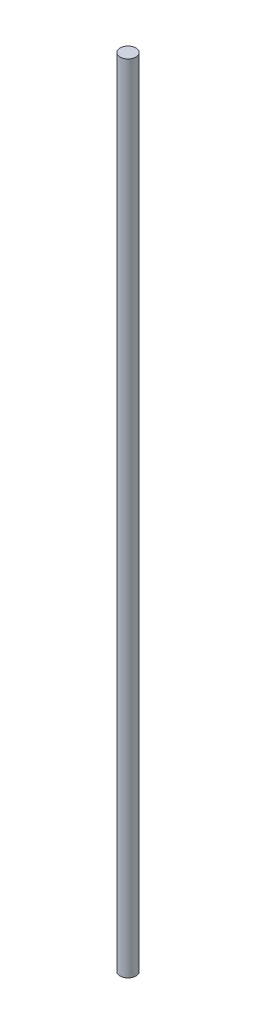
SolidWorks part; units mm, degrees
ref_plane "前视基准面" through (0, 0, 0) normal (0, 0, 1) x (1, 0, 0)
ref_plane "上视基准面" through (0, 0, 0) normal (0, 1, 0) x (1, 0, 0)
ref_plane "右视基准面" through (0, 0, 0) normal (1, 0, 0) x (0, 0, -1)
sketch "Sketch1" plane through (0, 0, 0) normal (0, 1, 0) x (1, 0, 0)
  circle A0 centre (0, 0) radius 4
  dimension "D1" = 8
extrude "Boss-Extrude1" add sketch "Sketch1" along normal blind 400
cosmetic thread "Cosmetic Thread1" parameters "D2"=6.647
